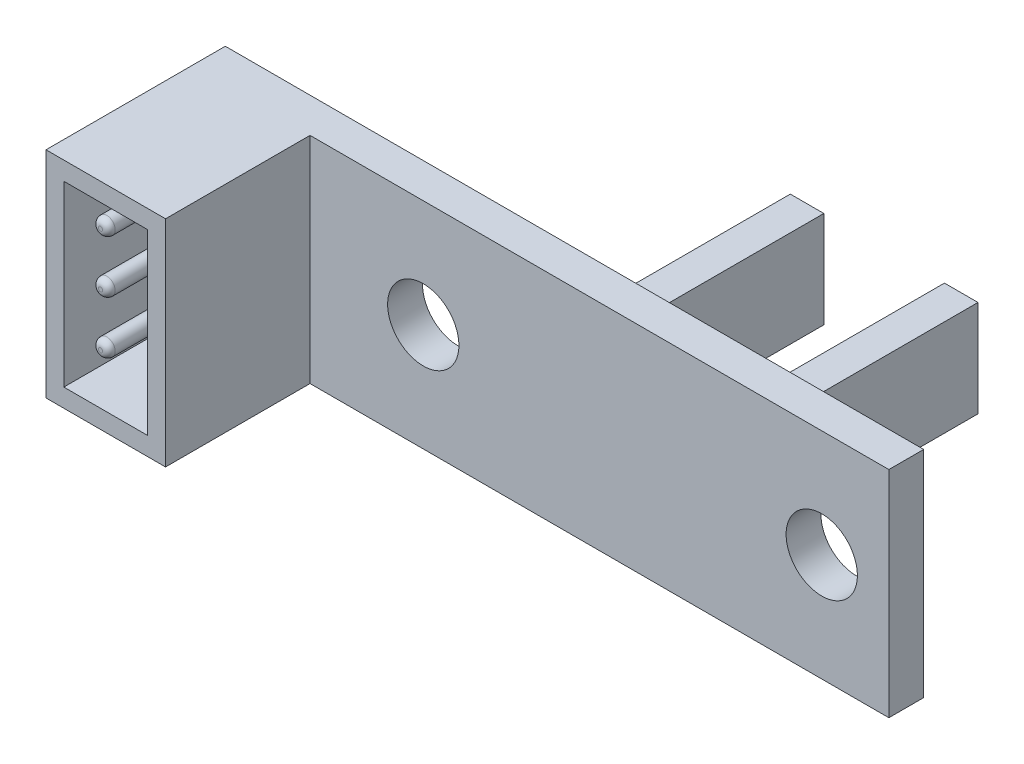
SolidWorks part; units mm, degrees
ref_plane "Спереди" through (0, 0, 0) normal (0, 0, 1) x (1, 0, 0)
ref_plane "Сверху" through (0, 0, 0) normal (0, 1, 0) x (1, 0, 0)
ref_plane "Справа" through (0, 0, 0) normal (1, 0, 0) x (0, 0, -1)
sketch "Эскиз1" plane through (0, 0, 0) normal (0, 0, 1) x (1, 0, 0)
  line L1 (0, 0) -> (33.3, 0)
  line L2 (0, 0) -> (0, 10.25)
  line L3 (0, 10.25) -> (33.3, 10.25)
  line L4 (33.3, 0) -> (33.3, 10.25)
  dimension "D1" = 33.3
  dimension "D2" = 10.25
extrude "Бобышка-Вытянуть1" add sketch "Эскиз1" along normal blind 1.66
sketch "Эскиз2" plane through (0, 0, 1.66) normal (0, 0, 1) x (1, 0, 0)
  line L0 (0, 0) -> (33.3, 0) construction
  line L1 (0, 10.25) -> (5.7, 10.25)
  line L2 (0, 10.25) -> (0, 0)
  line L3 (0, 0) -> (5.7, 0)
  line L4 (5.7, 10.25) -> (5.7, 0)
  dimension "D1" = 5.7
extrude "Бобышка-Вытянуть3" add sketch "Эскиз2" along normal offset from surface (6.89 mm away) 8.55 up to face at (16.65, 5.125, 0)
sketch "Эскиз3" plane through (0, 0, 8.55) normal (0, 0, 1) x (1, 0, 0)
  line L0 (0, 10.25) -> (5.7, 10.25) construction
  line L1 (0.85, 9.375) -> (4.85, 9.375)
  line L2 (0.85, 9.375) -> (0.85, 0.875)
  line L3 (0.85, 0.875) -> (4.85, 0.875)
  line L4 (4.85, 9.375) -> (4.85, 0.875)
  line L5 (0, 0) -> (0, 10.25) construction
  point P4 (2.85, 9.375)
  point P7 (2.85, 10.25)
  point P8 (0.85, 5.125)
  point P11 (0, 5.125)
  dimension "D1" = 0
  dimension "D2" = 0
  dimension "D3" = 4
  dimension "D4" = 8.5
extrude "Вырез-Вытянуть1" cut sketch "Эскиз3" against normal blind 6.05
sketch "Эскиз4" plane through (0, 0, 2.5) normal (0, 0, 1) x (1, 0, 0)
  circle A0 centre (2.0508, 5.231) radius 0.4
  circle A1 centre (2.0508, 7.741) radius 0.4
  circle A2 centre (2.0508, 2.721) radius 0.4
  dimension "D3" = 0.8
  dimension "D1" = 2.51
  dimension "D2" = 2.51
extrude "Бобышка-Вытянуть4" add sketch "Эскиз4" along normal blind 5.5
fillet "Скругление1" radius 0.3 3 edges at (2.4508, 2.721, 8) (2.4508, 5.231, 8) (2.4508, 7.741, 8)
sketch "Эскиз5" plane through (0, 0, 1.66) normal (0, 0, 1) x (1, 0, 0)
  line L0 (33.3, 0) -> (33.3, 10.25) construction
  circle A0 centre (11.1, 5.125) radius 1.7
  circle A1 centre (30.1, 5.125) radius 1.7
  point P4 (0, 0)
  point P7 (33.3, 5.125)
  dimension "D2" = 3.4
  dimension "D1" = 0
  dimension "D3" = 3.2
  dimension "D4" = 19
extrude "Вырез-Вытянуть2" cut sketch "Эскиз5" against normal through all
sketch "Эскиз6" plane through (0, 0, 0) normal (0, 0, -1) x (-1, 0, 0)
  line L0 (-33.3, 0) -> (-33.3, 10.25) construction
  line L1 (-25.7, 7.425) -> (-24.1, 7.425)
  line L2 (-25.7, 7.425) -> (-25.7, 2.825)
  line L3 (-25.7, 2.825) -> (-24.1, 2.825)
  line L4 (-24.1, 7.425) -> (-24.1, 2.825)
  line L5 (-18.35, 7.425) -> (-16.75, 7.425)
  line L6 (-18.35, 7.425) -> (-18.35, 2.825)
  line L7 (-18.35, 2.825) -> (-16.75, 2.825)
  line L8 (-16.75, 7.425) -> (-16.75, 2.825)
  point P8 (-25.7, 5.125)
  point P11 (-33.3, 5.125)
  dimension "D1" = 0
  dimension "D2" = 4.6
  dimension "D3" = 1.6
  dimension "D4" = 9.2
  dimension "D5" = 16.55
  dimension "D6" = 8.95
extrude "Бобышка-Вытянуть5" add sketch "Эскиз6" along normal offset from surface (10.19 mm away) 11.85 up to face at (12.8, 5.125, 1.66)
